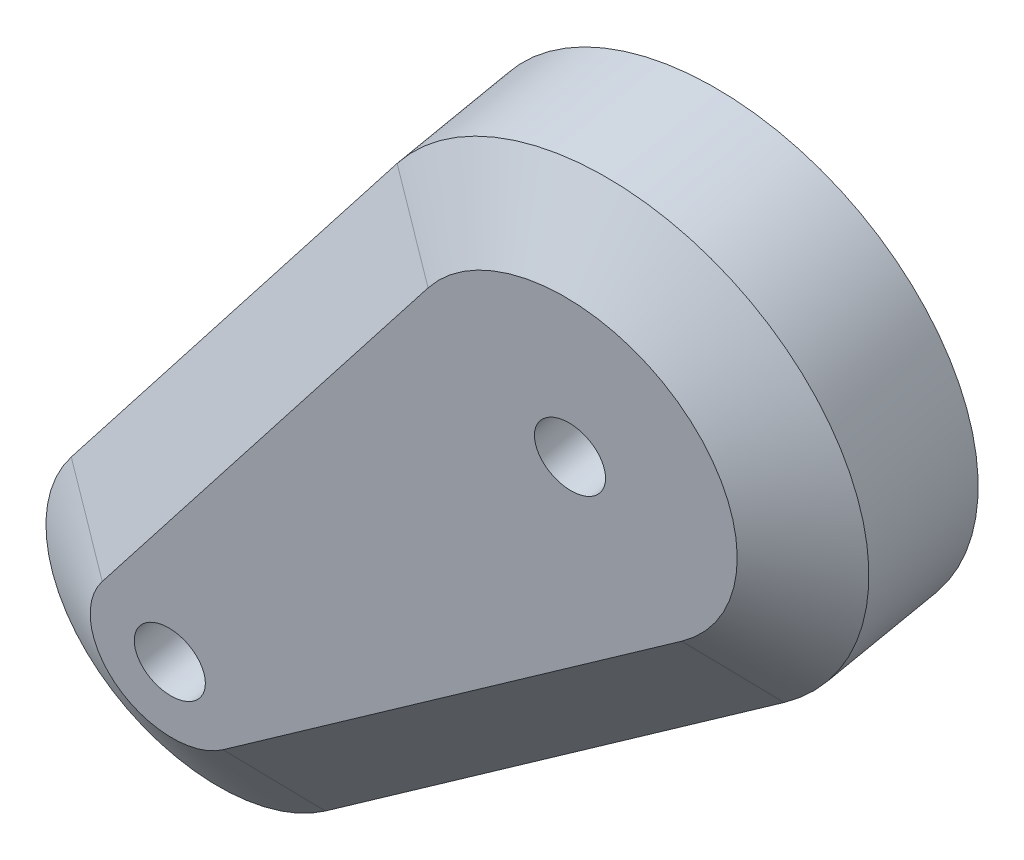
SolidWorks part; units mm, degrees
ref_plane "Front Plane" through (0, 0, 0) normal (0, 0, 1) x (1, 0, 0)
ref_plane "Top Plane" through (0, 0, 0) normal (0, 1, 0) x (1, 0, 0)
ref_plane "Right Plane" through (0, 0, 0) normal (1, 0, 0) x (0, 0, -1)
sketch "Sketch3" plane through (1.2592, -2.3057, 18.4805) normal (0.0675, -0.1235, 0.99) x (0.9977, 0.0042, -0.0675)
  line L1 (135.3096, -139.4246) -> (150.3535, -120.3976)
  line L2 (140.9053, -145.3063) -> (160.6579, -131.2285)
  arc A0 (135.3096, -139.4246) -> (140.9053, -145.3063) centre (138.5258, -141.9675) ccw
  circle A1 centre (138.5258, -141.9675) radius 1.2744 construction
  arc A2 (160.6579, -131.2285) -> (150.3535, -120.3976) centre (156.2759, -125.0802) ccw
  arc A3 (157.1222, -132.2806) -> (161.8607, -120.4571) centre (156.2759, -125.0802) ccw construction
  arc A4 (135.9065, -139.2144) -> (141.145, -144.7206) centre (138.5258, -141.9675) ccw construction
  dimension "D1" = 0.3
  dimension "D2" = 0.3
extrude "Boss-Extrude1" add sketch "Sketch3" along normal blind 2.5
sketch "Sketch4" plane through (1.4278, -2.6145, 20.9556) normal (0.0675, -0.1235, 0.99) x (0.9977, 0.0042, -0.0675)
  line L0 (156.2759, -125.0802) -> (138.5258, -141.9675) construction
  line L1 (142.3563, -147.3422) -> (162.1088, -133.2643)
  line L4 (140.9053, -145.3063) -> (160.6579, -131.2285) construction
  line L5 (150.3535, -120.3976) -> (135.3096, -139.4246) construction
  line L6 (140.9053, -145.3063) -> (160.6579, -131.2285)
  line L7 (150.3535, -120.3976) -> (135.3096, -139.4246)
  line L8 (148.3924, -118.847) -> (133.3485, -137.8741)
  arc A1 (135.3096, -139.4246) -> (140.9053, -145.3063) centre (138.5258, -141.9675) ccw construction
  arc A4 (160.6579, -131.2285) -> (150.3535, -120.3976) centre (156.2759, -125.0802) ccw construction
  arc A5 (135.3096, -139.4246) -> (140.9053, -145.3063) centre (138.5258, -141.9675) ccw
  arc A6 (160.6579, -131.2285) -> (150.3535, -120.3976) centre (156.2759, -125.0802) ccw
  arc A7 (133.3485, -137.8741) -> (142.3563, -147.3422) centre (138.5258, -141.9675) ccw
  arc A8 (162.1088, -133.2643) -> (148.3924, -118.847) centre (156.2759, -125.0802) ccw
  dimension "D1" = 2.5
extrude "Boss-Extrude2" add sketch "Sketch4" against normal blind 7
sketch "Sketch5" plane through (1.2592, -2.3057, 18.4805) normal (-0.0675, 0.1235, -0.99) x (-0.9977, -0.0084, 0.0669)
  line L0 (-155.7496, -125.7349) -> (-137.9287, -142.5476) construction
  line L1 (-137.9287, -142.5476) -> (-133.128, -147.0767) construction
  circle A0 centre (-155.7496, -125.7349) radius 1.4
  circle A1 centre (-137.9287, -142.5476) radius 1.4
  arc A4 (-149.8469, -121.0275) -> (-160.1057, -131.9015) centre (-155.7496, -125.7349) ccw construction
  arc A5 (-141.7367, -147.9383) -> (-132.7687, -138.4325) centre (-137.9287, -142.5476) ccw construction
  dimension "D1" = 2.8
  dimension "D2" = 24.5
extrude "Cut-Extrude1" cut sketch "Sketch5" against normal through all
chamfer "Chamfer1" distance 2 angle 60 4 edges at (141.4387, -129.4011, -4.4027) (134.2526, -147.4479, -6.1647) (164.1162, -119.1767, -4.6723) (152.7248, -141.2046, -6.6444)
move or copy body "Body-Move/Copy2" [suppressed] bodies to move or copy 103 parameters "D1"=0, "D2"=0, "D3"=0
move or copy body "Body-Move/Copy1" [suppressed] bodies to move or copy 103 parameters "D1"=0, "D2"=0, "D3"=0
